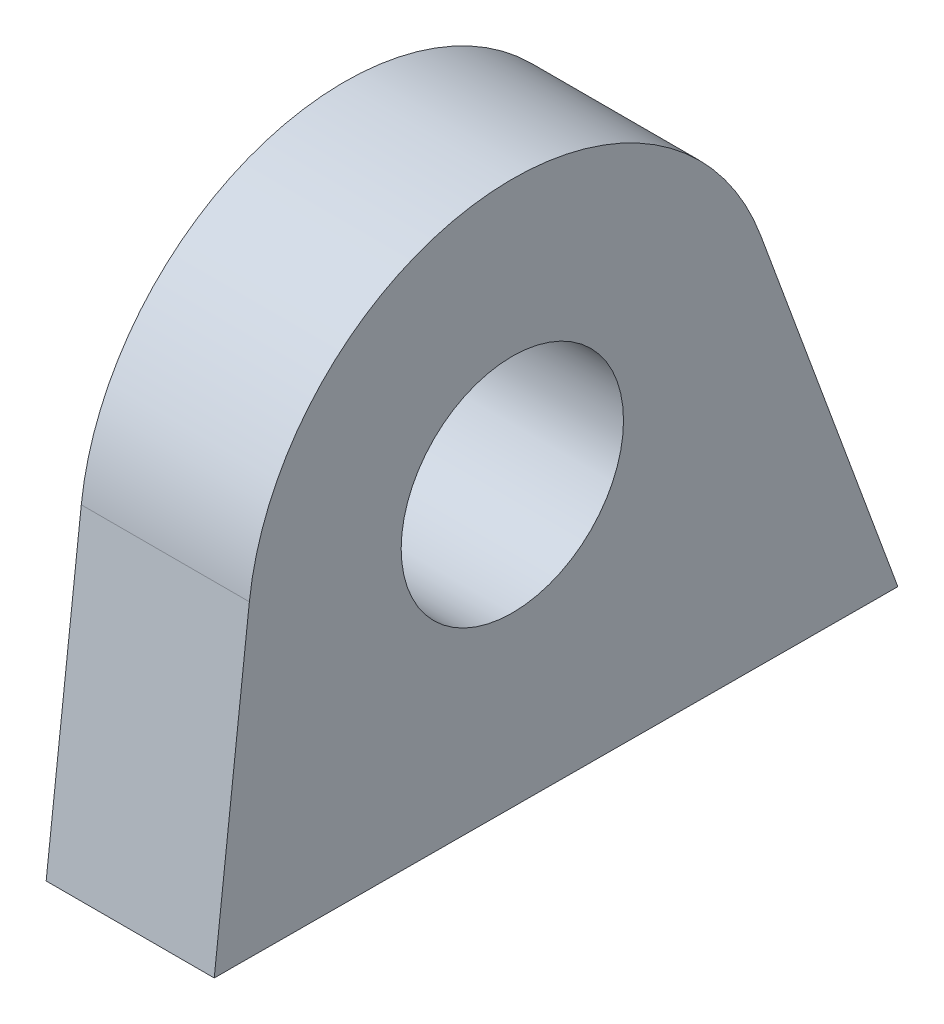
SolidWorks part; units mm, degrees
material "AISI 4130 Steel, normalized at 870C"
ref_plane "Front Plane" through (0, 0, 0) normal (0, 0, 1) x (1, 0, 0)
ref_plane "Top Plane" through (0, 0, 0) normal (0, 1, 0) x (1, 0, 0)
ref_plane "Right Plane" through (0, 0, 0) normal (1, 0, 0) x (0, 0, -1)
sketch "Sketch1" plane through (71.2924, 0, 0) normal (1, 0, 0) x (0, 0, -1)
  line L0 (752.3933, 358.3563) -> (751.0657, 346.711)
  line L1 (1092.329, 344.8118) -> (734.1363, 346.8052) construction
  line L2 (751.0657, 346.711) -> (776.8943, 346.6005)
  line L3 (771.7136, 360.6774) -> (782.0751, 332.5236) construction
  line L4 (776.8943, 346.6005) -> (771.7136, 360.6774)
  line L5 (749.4484, 332.5236) -> (752.3933, 358.3563) construction
  arc A0 (771.7136, 360.6774) -> (752.3933, 358.3563) centre (762.329, 357.2236) ccw
  circle A1 centre (762.329, 357.2236) radius 4.2
  point P16 (0, 0)
  point P17 (761.333, 357.2236)
  dimension "D1" = 10
  dimension "D2" = 8.4
extrude "Boss-Extrude1" add sketch "Sketch1" along normal blind 6.35
